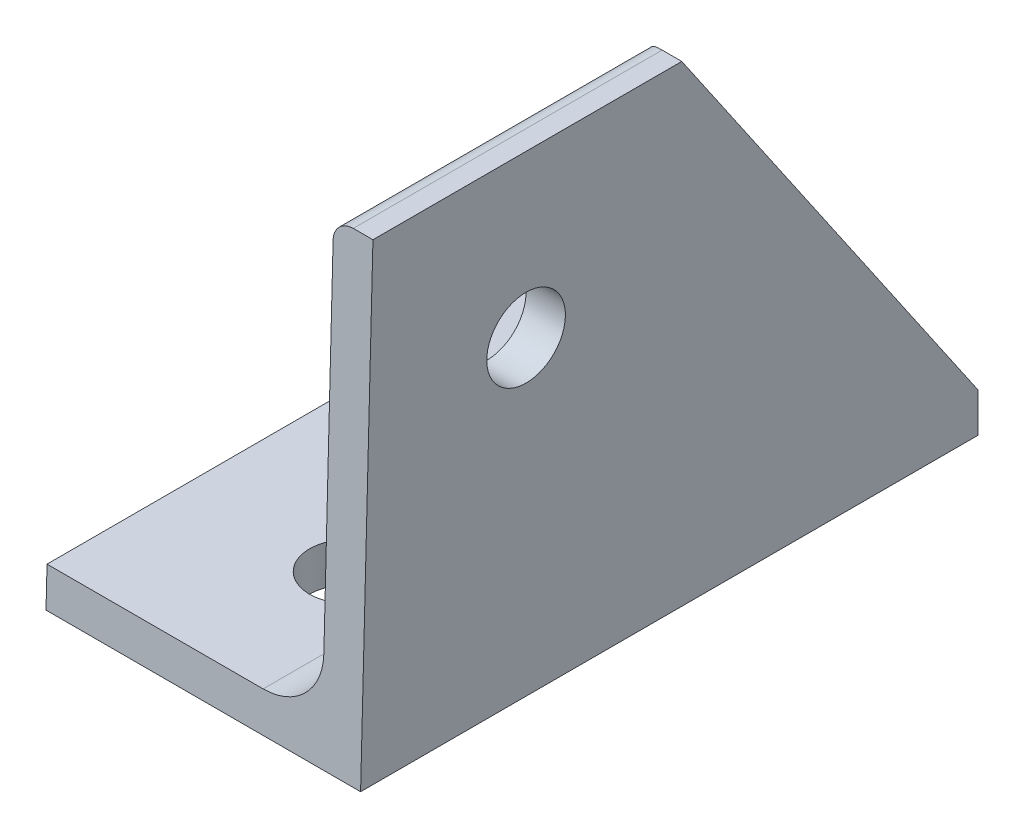
SolidWorks part; units mm, degrees
ref_plane "Front Plane" through (0, 0, 0) normal (0, 0, 1) x (1, 0, 0)
ref_plane "Top Plane" through (0, 0, 0) normal (0, 1, 0) x (1, 0, 0)
ref_plane "Right Plane" through (0, 0, 0) normal (1, 0, 0) x (0, 0, -1)
sketch "Sketch0" plane through (0, 0, 0) normal (0, 0, 1) x (1, 0, 0)
  line L0 (-19.05, -19.05) -> (19.05, -19.05)
  line L1 (19.05, -19.05) -> (19.05, 19.05)
  line L2 (19.05, 0) -> (0, 0) construction
  line L3 (0, 0) -> (0, -19.05) construction
  line L4 (15.875, -11.0998) -> (15.875, 19.05) construction
  line L5 (11.0998, -15.875) -> (-19.05, -15.875) construction
  arc A0 (15.875, -11.0998) -> (11.0998, -15.875) centre (11.0998, -11.0998) cw
  point P3 (14.4764, -14.4764)
  dimension "Inside Corner Radius" = 4.7752
  dimension "Outside Height" = 38.1
  dimension "Inside Height" = 34.925
  dimension "Inside Width" = 34.925
  dimension "Wall Thickness" = 3.175
  dimension "D1" = 3.175
  dimension "Outside Width" = 38.1
sketch "Sketch1" plane through (0, 0, 0) normal (1, 0, 0) x (0, 0, -1)
  line L0 (25.4, 0) -> (-25.4, 0)
  point P4 (0, 0)
  dimension "Length" = 50.8
sketch "Sketch2" plane through (0, 0, 0) normal (0, 0, 1) x (1, 0, 0)
  line L0 (-19.05, -19.05) -> (19.05, -19.05)
  line L1 (19.05, -19.05) -> (19.05, 19.05)
  line L2 (19.05, 19.05) -> (15.875, 19.05) construction
  line L3 (15.875, 17.4625) -> (15.875, -11.0998)
  line L4 (11.0998, -15.875) -> (-17.4625, -15.875)
  line L5 (-19.05, -19.05) -> (-19.05, -15.875) construction
  line L6 (17.4625, 19.05) -> (19.05, 19.05)
  line L7 (-19.05, -17.4625) -> (-19.05, -19.05)
  line L8 (19.05, 0) -> (0, 0) construction
  line L9 (0, 0) -> (0, -19.05) construction
  arc A0 (15.875, 17.4625) -> (17.4625, 19.05) centre (17.4625, 17.4625) cw
  arc A1 (-19.05, -17.4625) -> (-17.4625, -15.875) centre (-17.4625, -17.4625) cw
  arc A2 (15.875, -11.0998) -> (11.0998, -15.875) centre (11.0998, -11.0998) cw
  dimension "Inside Radius" = 4.7752
  dimension "Height" = 38.1
  dimension "Width" = 38.1
  dimension "Thickness" = 3.175
extrude "Boss-Extrude1" add sketch "Sketch2" along normal mid plane 50.8
sketch "Break Locations" plane through (0, 0, 0) normal (1, 0, 0) x (0, 0, -1)
  line L0 (13.462, 0) -> (-13.462, 0)
  line L1 (-25.4, -19.05) -> (-25.4, 19.05) construction
  line L2 (25.4, -19.05) -> (25.4, 19.05) construction
  point P0 (6.985, 0)
  point P1 (-6.985, 0)
  point P10 (0, 0)
  point P11 (-13.462, 0)
  point P13 (13.462, 0)
  dimension "D1" = 32.385
  dimension "D2" = 32.385
  dimension "D3" = 38.862
sketch "Sketch3" plane through (0, -19.05, 0) normal (0, -1, 0) x (1, 0, 0)
  line L0 (19.05, 25.4) -> (6.35, 25.4) construction
  line L1 (-19.05, 25.4) -> (19.05, 25.4) construction
  line L2 (6.35, 25.4) -> (6.35, 12.7) construction
  line L3 (6.35, 12.7) -> (6.35, -12.7) construction
  line L4 (-19.05, 25.4) -> (-6.35, 25.4)
  line L5 (-6.35, 25.4) -> (-6.35, -25.4)
  line L6 (-19.05, -25.4) -> (19.05, -25.4) construction
  line L7 (-6.35, -25.4) -> (-19.05, -25.4)
  line L8 (-19.05, -25.4) -> (-19.05, 25.4)
  circle A0 centre (6.35, 12.7) radius 3.175
  circle A1 centre (6.35, -12.7) radius 3.175
  dimension "D4" = 12.7
  dimension "D1" = 12.7
  dimension "D2" = 12.7
  dimension "D3" = 25.4
extrude "Cut-Extrude1" cut sketch "Sketch3" against normal through all
sketch "Sketch12" plane through (19.05, 0, 0) normal (1, 0, 0) x (0, 0, -1)
  line L1 (-23.4518, 19.05) -> (1.4842, 19.05)
  line L2 (-25.4, 19.05) -> (25.4, 19.05) construction
  line L3 (-25.4, -19.05) -> (25.4, -19.05) construction
  line L9 (0, 19.05) -> (0, -19.05) construction
  line L10 (25.4, -19.05) -> (-24.4495, -19.05)
  line L11 (25.4, -15.875) -> (25.4, -19.05)
  line L12 (1.4842, 19.05) -> (25.4, -15.875)
  line L14 (-23.4518, 19.05) -> (-24.4495, -19.05)
extrude "Cut-Extrude2" cut sketch "Sketch12" against normal through all flip side to cut
sketch "Sketch13" plane through (19.05, 0, 0) normal (1, 0, 0) x (0, 0, -1)
  line L2 (-10.7562, 18.7176) -> (-11.0886, 6.0219) construction
  circle A2 centre (-11.0886, 6.0219) radius 3.175
extrude "Cut-Extrude3" cut sketch "Sketch13" against normal through all
sketch "Sketch14" plane through (0, -15.875, 0) normal (0, 1, 0) x (1, 0, 0)
  circle A0 centre (6.35, 12.7) radius 6.35
  circle A1 centre (6.35, -12.7) radius 6.35
extrude "Cut-Extrude4" cut sketch "Sketch14" along normal blind 2.54
equation "\"D1@Break Locations\" = .85 * \"Height@Sketch2\""
equation "\"D2@Break Locations\"=\"D1@Break Locations\""
equation "\"Thickness@Sketch2\"=\"wall thickness@sketch0\""
equation "\"Height@Sketch2\"=\"outside height@sketch0\""
equation "\"Width@Sketch2\"=\"outside width@sketch0\""
equation "\"Inside Radius@Sketch2\"=\"inside corner radius@sketch0\""
equation "\"Length@Boss-Extrude1\"=\"length@sketch1\""
equation "\"D3@Break Locations\"=\"D2@Break Locations\"*1.2"
equation "\"D1@Sketch0\"=\"Wall Thickness@Sketch0\""
